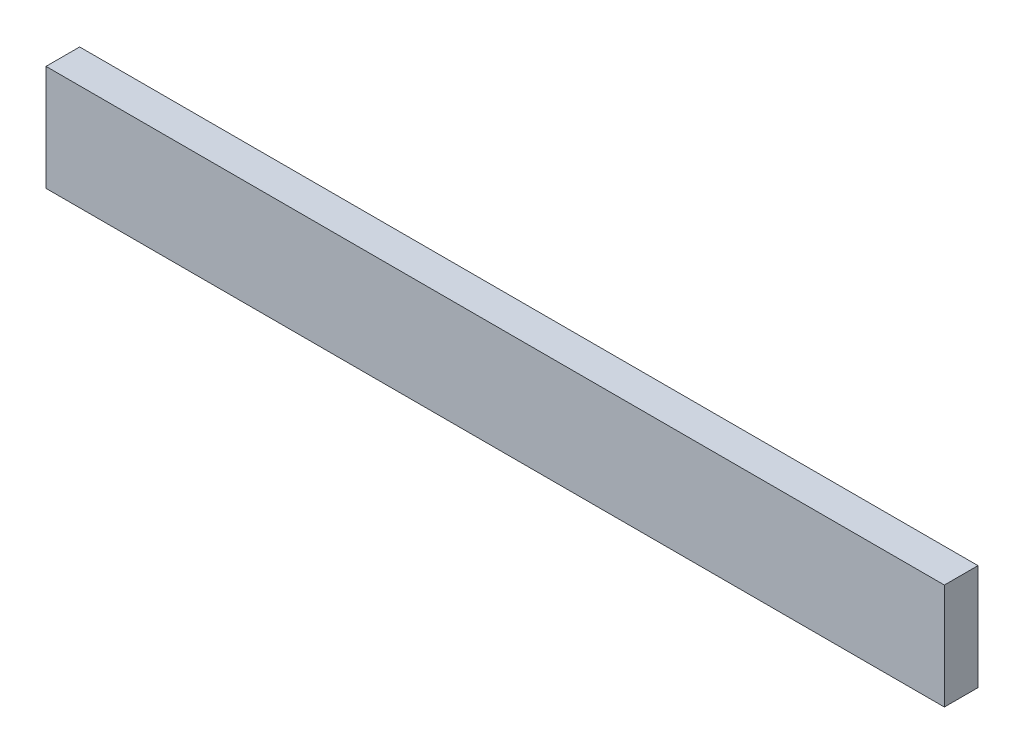
SolidWorks part; units mm, degrees
ref_plane "Plano frontal" through (0, 0, 0) normal (0, 0, 1) x (1, 0, 0)
ref_plane "Plano superior" through (0, 0, 0) normal (0, 1, 0) x (1, 0, 0)
ref_plane "Plano direito" through (0, 0, 0) normal (1, 0, 0) x (0, 0, -1)
sketch "Esboço1" plane through (0, 0, 0) normal (0, 0, 1) x (1, 0, 0)
  line L1 (-46.1032, 20.4143) -> (0.6468, 20.4143)
  line L2 (-46.1032, 20.4143) -> (-46.1032, 14.9143)
  line L3 (-46.1032, 14.9143) -> (0.6468, 14.9143)
  line L4 (0.6468, 20.4143) -> (0.6468, 14.9143)
extrude "Ressalto-extrusão1" add sketch "Esboço1" along normal blind 1.75
